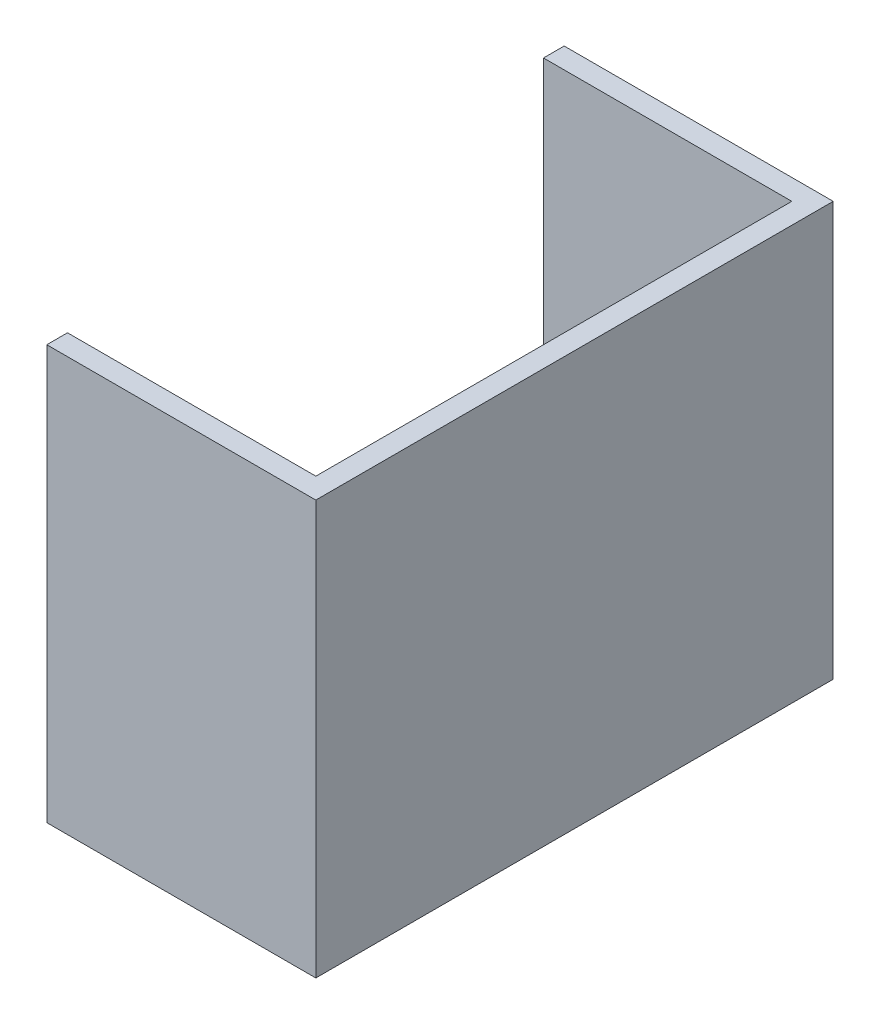
SolidWorks part; units mm, degrees
ref_plane "정면" through (0, 0, 0) normal (0, 0, 1) x (1, 0, 0)
ref_plane "윗면" through (0, 0, 0) normal (0, 1, 0) x (1, 0, 0)
ref_plane "우측면" through (0, 0, 0) normal (1, 0, 0) x (0, 0, -1)
sketch "스케치15" plane through (0, 0, 0) normal (0, 1, 0) x (1, 0, 0)
  line L1 (-6, -12.5) -> (7, -12.5)
  line L2 (-6, -12.5) -> (-6, 12.5)
  line L3 (-6, 12.5) -> (7, 12.5)
  line L4 (7, -12.5) -> (7, 12.5)
  dimension "D1" = 13
  dimension "D2" = 25
extrude "보스-돌출4" add sketch "스케치15" along normal blind 20
sketch "스케치16" plane through (0, 0, 0) normal (0, 1, 0) x (1, 0, 0)
  line L1 (-6, 11.5) -> (6, 11.5)
  line L2 (-6, 11.5) -> (-6, -11.5)
  line L3 (-6, -11.5) -> (6, -11.5)
  line L4 (6, 11.5) -> (6, -11.5)
  line L5 (-6, -12.5) -> (7, -12.5) construction
  line L6 (-6, 12.5) -> (-6, -12.5) construction
  dimension "D1" = 12
  dimension "D2" = 23
  dimension "D3" = 1
extrude "컷-돌출47" cut sketch "스케치16" along normal through all from offset 1
sketch "스케치17" plane through (0, 0, 0) normal (0, 1, 0) x (1, 0, 0)
  line L0 (-6, -11.5) -> (6, -11.5) construction
  line L2 (-6, 11.5) -> (-6, -11.5) construction
  line L3 (-6, 3.5) -> (6, 3.5)
  line L4 (-6, 3.5) -> (-6, -5.5)
  line L6 (6, 3.5) -> (6, -5.5)
  arc A0 (-6, -5.5) -> (6, -5.5) centre (0, -5.5) ccw
  dimension "D1" = 12
  dimension "D2" = 12
  dimension "D3" = 9
extrude "컷-돌출48" cut sketch "스케치17" along normal through all
